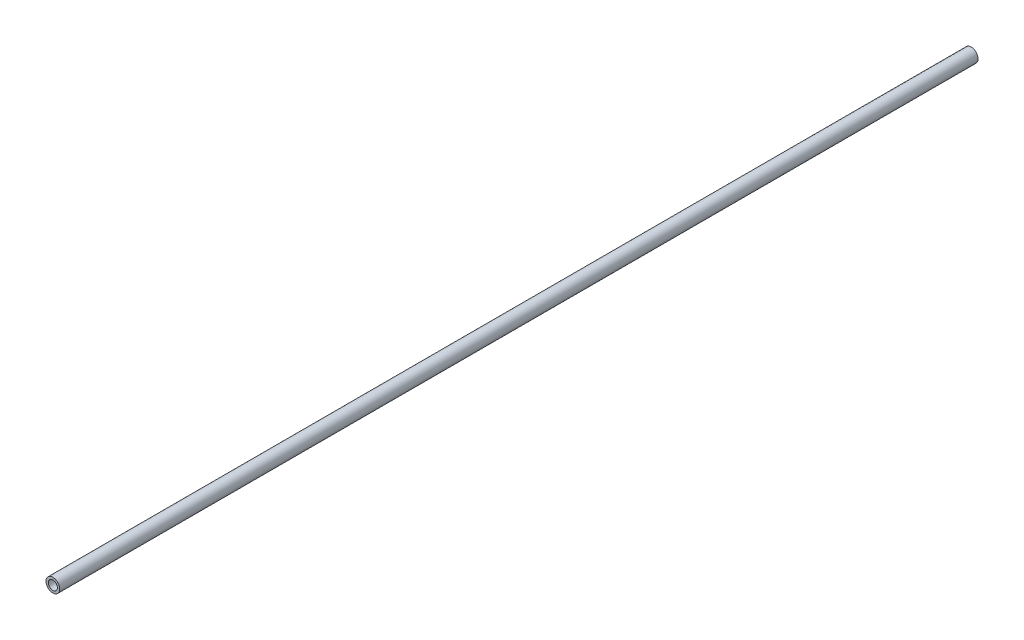
SolidWorks part; units mm, degrees
material "3003-O"
ref_plane "Front" through (0, 0, 0) normal (0, 0, 1) x (1, 0, 0)
ref_plane "Top" through (0, 0, 0) normal (0, 1, 0) x (1, 0, 0)
ref_plane "Right" through (0, 0, 0) normal (1, 0, 0) x (0, 0, -1)
sketch "Sketch3" plane through (0, 0, 0) normal (0, 0, 1) x (1, 0, 0)
  circle A0 centre (0, 0) radius 9.525
  circle A1 centre (0, 0) radius 6.35
  dimension "D1" = 19.05
  dimension "D2" = 12.7
extrude "Boss-Extrude1" add sketch "Sketch3" along normal blind 1282.7
